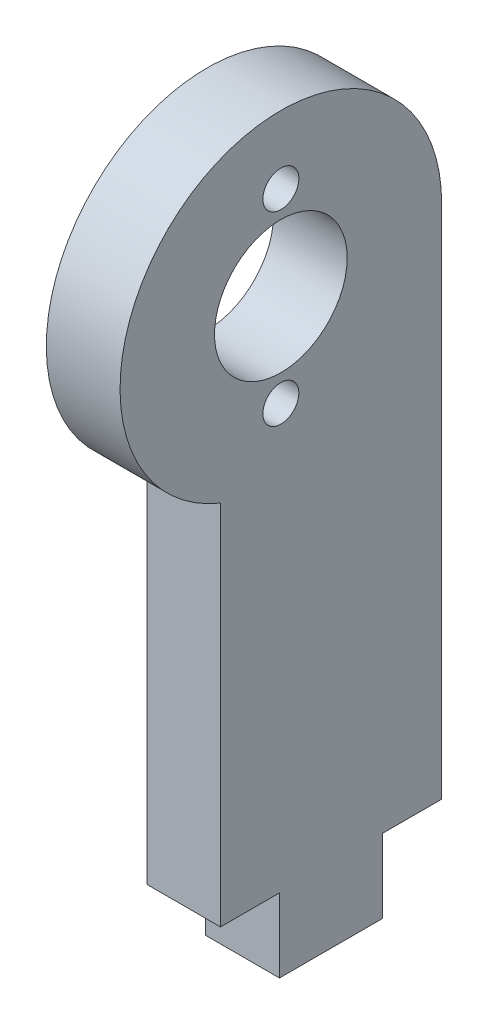
SolidWorks part; units mm, degrees
ref_plane "Front" through (0, 0, 0) normal (0, 0, 1) x (1, 0, 0)
ref_plane "Top" through (0, 0, 0) normal (0, 1, 0) x (1, 0, 0)
ref_plane "Right" through (0, 0, 0) normal (1, 0, 0) x (0, 0, -1)
sketch "Sketch1" plane through (0, 0, 0) normal (1, 0, 0) x (0, 0, -1)
  line L1 (5.08, 0) -> (13.97, 0)
  line L2 (0, 6.35) -> (0, 37.9632)
  line L3 (19.05, 6.35) -> (13.97, 6.35)
  line L4 (19.05, 6.35) -> (19.05, 50.8)
  line L7 (13.97, 6.35) -> (13.97, 0)
  line L8 (0, 6.35) -> (5.08, 6.35)
  line L11 (5.08, 6.35) -> (5.08, 0)
  arc A0 (19.05, 50.8) -> (0, 37.9632) centre (5.2, 50.8) ccw
  circle A1 centre (5.2, 50.8) radius 5.715
  dimension "D1" = 5.08
  dimension "D2" = 11.43
  dimension "D3" = 50.8
  dimension "D4" = 8.89
  dimension "D6" = 6.35
  dimension "D7" = 13.85
extrude "Boss-Extrude1" add sketch "Sketch1" along normal blind 6.35
hole_wizard "M2.5 Clearance Hole1" positions "Sketch4" profile "Sketch2" hole size "M2.5" standard "ANSI Metric" end condition through all
sketch "Sketch4" plane through (6.35, 0, 0) normal (1, 0, 0) x (0, 0, -1)
  line L0 (5.2, 58.8) -> (5.2, 42.8) construction
  line L2 (-0.515, 50.8) -> (10.915, 50.8) construction
  circle A0 centre (5.2, 50.8) radius 5.715 construction
  point P0 (5.2, 58.8)
  point P2 (5.2, 42.8)
  point P15 (5.2, 50.8)
  dimension "D1" = 16
sketch "Sketch2" plane through (6.35, 58.8, -5.2) normal (0, 1, 0) x (0, 0, -1)
  line L0 (0, 0) -> (0, 6.35)
  line L1 (0, 6.35) -> (1.55, 6.35)
  line L2 (1.55, 6.35) -> (1.55, 0)
  line L5 (1.55, 0) -> (0, 0)
  line L11 (0, -6.35) -> (0, 107.95) construction
  dimension "Thru Hole Dia." = 3.1
  dimension "Thru Hole Depth" = 6.35
